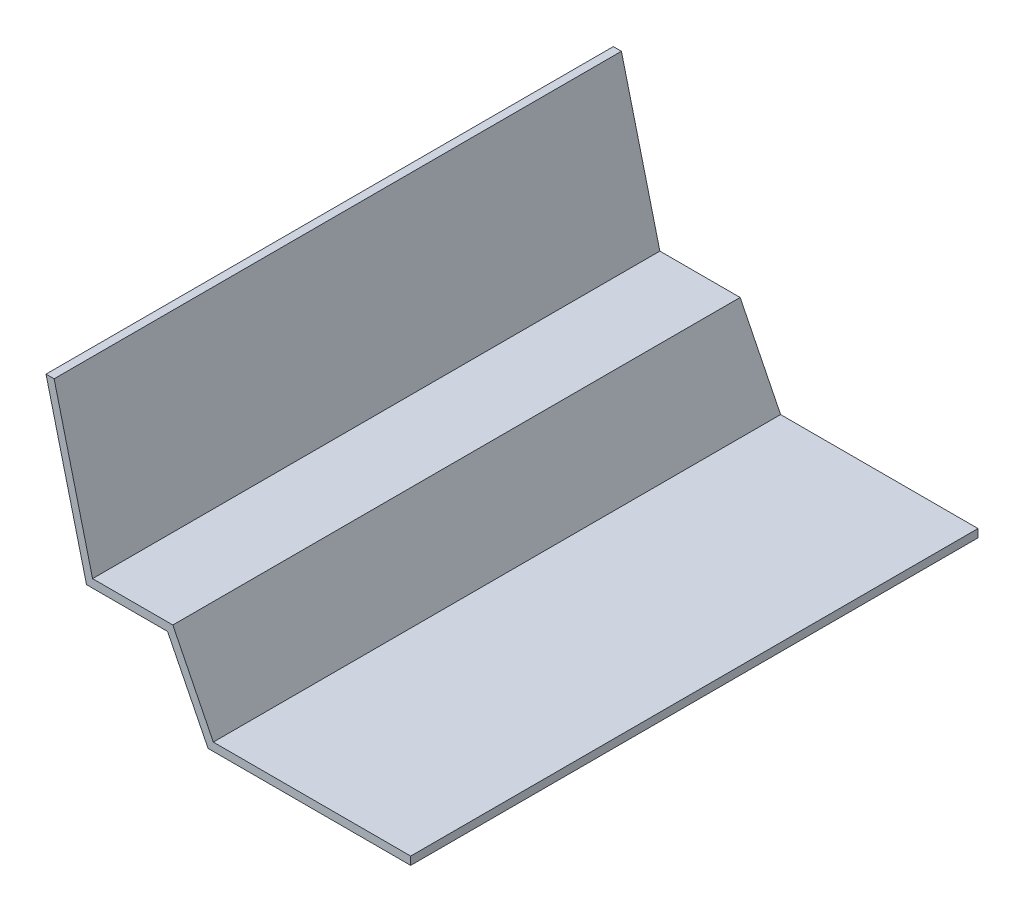
SolidWorks part; units mm, degrees
ref_plane "前视基准面" through (0, 0, 0) normal (0, 0, 1) x (1, 0, 0)
ref_plane "上视基准面" through (0, 0, 0) normal (0, 1, 0) x (1, 0, 0)
ref_plane "右视基准面" through (0, 0, 0) normal (1, 0, 0) x (0, 0, -1)
other "Configuration Table"
sketch "草图1" plane through (0, 0, 0) normal (0, 0, 1) x (1, 0, 0)
  line L0 (0, 0) -> (-50, 0)
  line L5 (-50, 0) -> (-60, 20)
  line L6 (-60, 20) -> (-80, 20)
  line L7 (-80, 20) -> (-90, 60)
  line L8 (-90, 60) -> (-88, 60)
  line L9 (-88, 60) -> (-78.5084, 22.0335)
  line L10 (-78.5084, 22.0335) -> (-58.7016, 22.0335)
  line L14 (0, 0) -> (0, 2)
  line L15 (-48.7136, 2) -> (-58.7016, 22.0335)
  line L16 (-48.7136, 2) -> (0, 2)
extrude "凸台-拉伸1" add sketch "草图1" along normal blind 140
